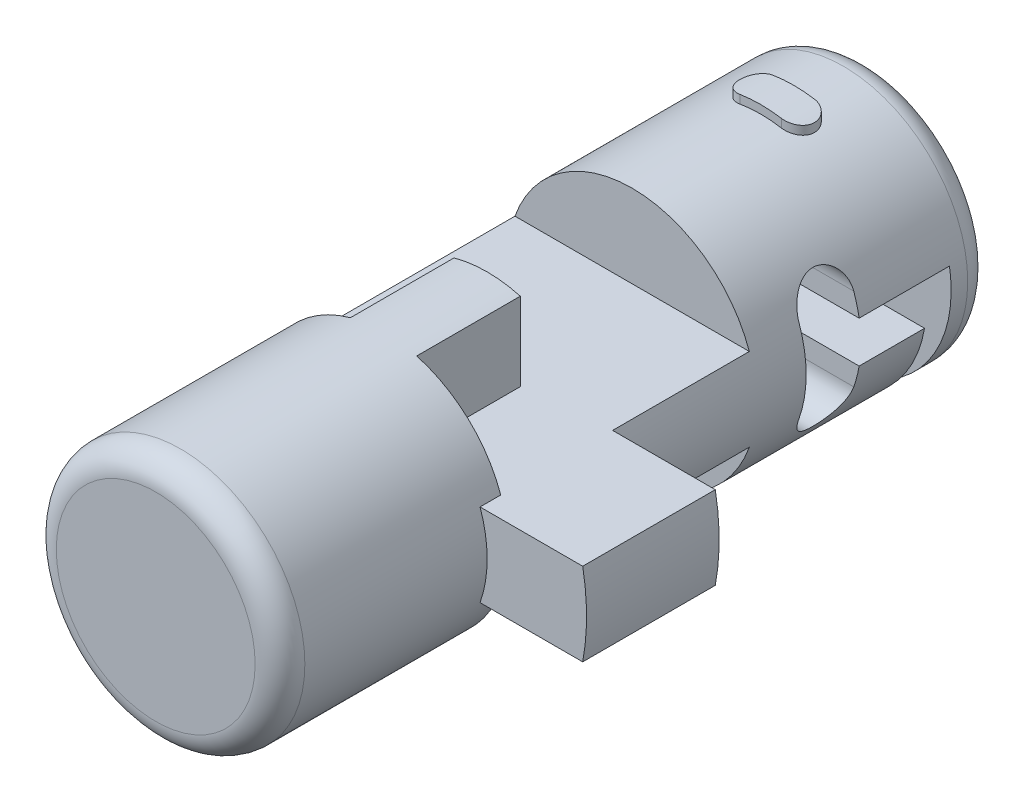
SolidWorks part; units mm, degrees
material "ABS"
ref_plane "Front Plane" through (0, 0, 0) normal (0, 0, 1) x (1, 0, 0)
ref_plane "Top Plane" through (0, 0, 0) normal (0, 1, 0) x (1, 0, 0)
ref_plane "Right Plane" through (0, 0, 0) normal (1, 0, 0) x (0, 0, -1)
sketch "Sketch1" plane through (0, 0, 0) normal (0, 0, 1) x (1, 0, 0)
  circle A0 centre (0, 0) radius 3.81
  dimension "D1" = 7.62
extrude "Boss-Extrude1" add sketch "Sketch1" along normal mid plane 21.844
ref_plane "Plane1" through (0, 3.81, 0) normal (0, 1, 0) x (1, 0, 0)
ref_plane "Plane2" through (0, 1.27, 0) normal (0, 1, 0) x (1, 0, 0)
sketch "Sketch2" plane through (0, 1.27, 0) normal (0, 1, 0) x (1, 0, 0)
  line L0 (-3.81, 10.922) -> (-3.81, -10.922) construction
  line L1 (-3.81, 3.683) -> (3.81, 3.683)
  line L2 (-3.81, 3.683) -> (-3.81, -3.937)
  line L3 (-3.81, -3.937) -> (-1.016, -3.937)
  line L4 (3.81, 3.683) -> (3.81, -3.937)
  line L5 (-3.81, 3.683) -> (3.81, -3.937) construction
  line L6 (-3.81, -3.937) -> (3.81, 3.683) construction
  line L7 (3.81, -10.922) -> (3.81, 10.922) construction
  line L8 (-3.81, -10.922) -> (3.81, -10.922) construction
  line L9 (1.016, -3.937) -> (3.81, -3.937)
  line L11 (-1.016, -3.937) -> (-1.016, -0.762)
  line L12 (-1.016, -0.762) -> (1.016, -0.762)
  line L13 (1.016, -3.937) -> (1.016, -0.762)
  line L14 (-1.016, -3.937) -> (1.016, -0.762) construction
  line L15 (-1.016, -0.762) -> (1.016, -3.937) construction
  point P4 (0, -0.127)
  point P15 (0, -2.3495)
  dimension "D1" = 6.985
  dimension "D2" = 7.62
  dimension "D3" = 3.175
  dimension "D4" = 2.032
  dimension "D5" = 1.016
extrude "Cut-Extrude1" cut sketch "Sketch2" along normal through all
mirror "Mirror1" about plane through (0, 0, 0) normal (0, 1, 0) of "Cut-Extrude1"
sketch "Sketch3" plane through (0, 0, 0) normal (1, 0, 0) x (0, 0, -1)
  line L0 (6.0458, -1.27) -> (6.0458, 1.27) construction
  line L1 (5.207, -1.27) -> (5.207, 1.27)
  line L2 (6.8847, -1.27) -> (6.8847, -0.635)
  line L3 (6.8847, 0.635) -> (9.652, 0.635)
  line L4 (9.652, 0.635) -> (9.652, -3.81)
  line L5 (3.683, -3.81) -> (10.922, -3.81) construction
  line L6 (9.652, -3.81) -> (8.89, -3.81)
  line L7 (8.89, -3.81) -> (8.89, -0.635)
  line L8 (8.89, -0.635) -> (6.8847, -0.635)
  line L9 (-10.922, 0) -> (10.922, 0) construction
  line L10 (10.922, -3.81) -> (10.922, 3.81) construction
  line L11 (6.8847, 0.635) -> (6.8847, 1.27)
  arc A0 (5.207, -1.27) -> (6.8847, -1.27) centre (6.0458, -1.27) ccw
  arc A1 (6.8847, 1.27) -> (5.207, 1.27) centre (6.0458, 1.27) ccw
  point P2 (6.0458, 0)
  dimension "D1" = 2.54
  dimension "D2" = 1.524
  dimension "D3" = 1.27
  dimension "D4" = 0.635
  dimension "D5" = 1.27
  dimension "D6" = 0.762
  dimension "D7" = 1.6777
extrude "Cut-Extrude2" cut sketch "Sketch3" against normal mid plane 21.844 contours A1 L1 A0 L2 L8 L7 L6 L4 L3 L11
sketch "Sketch4" plane through (0, 0, 0) normal (1, 0, 0) x (0, 0, -1)
  line L0 (-3.937, 1.27) -> (3.683, 1.27) construction
  line L1 (-0.508, 1.27) -> (-4.572, 1.27)
  line L2 (-0.508, 1.27) -> (-0.508, -1.27)
  line L3 (-0.508, -1.27) -> (-4.572, -1.27)
  line L4 (-4.572, 1.27) -> (-4.572, -1.27)
  line L5 (-0.508, 1.27) -> (-4.572, -1.27) construction
  line L6 (-0.508, -1.27) -> (-4.572, 1.27) construction
  line L9 (3.683, -1.27) -> (-3.937, -1.27) construction
  line L10 (-10.922, 3.81) -> (-10.922, -3.81) construction
  point P4 (-2.54, 0)
  dimension "D1" = 4.064
  dimension "D2" = 6.35
extrude "Boss-Extrude2" add sketch "Sketch4" along normal offset from surface (6.7394 mm away) 3.048
sketch "Sketch5" plane through (0, 0.635, 0) normal (0, 1, 0) x (1, 0, 0)
  line L0 (-0.635, 8.128) -> (0.635, 8.128) construction
  line L1 (-0.635, 8.636) -> (0.635, 8.636)
  line L2 (-0.635, 7.62) -> (0.635, 7.62)
  line L3 (3.81, 10.922) -> (-3.81, 10.922) construction
  arc A0 (-0.635, 8.636) -> (-0.635, 7.62) centre (-0.635, 8.128) ccw
  arc A1 (0.635, 7.62) -> (0.635, 8.636) centre (0.635, 8.128) ccw
  point P2 (0, 8.128)
  dimension "D2" = 0.508
  dimension "D1" = 1.27
  dimension "D3" = 2.286
extrude "Boss-Extrude3" add sketch "Sketch5" along normal offset from surface (3.3791 mm away) 0.254
mirror "Mirror2" about plane through (0, 0, 0) normal (0, 1, 0) of "Boss-Extrude3"
fillet "Fillet1" radius 0.762 2 edges at (3.81, 0, -10.922) (3.81, 0, 10.922)
